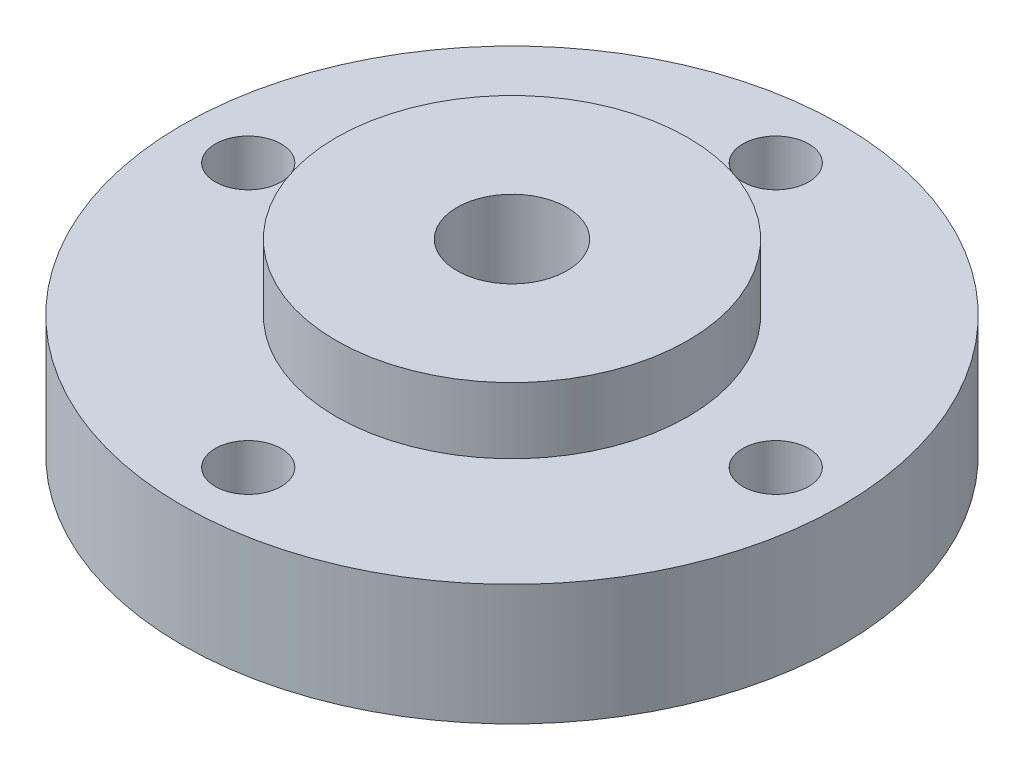
SolidWorks part; units mm, degrees
ref_plane "前视基准面" through (0, 0, 0) normal (0, 0, 1) x (1, 0, 0)
ref_plane "上视基准面" through (0, 0, 0) normal (0, 1, 0) x (1, 0, 0)
ref_plane "右视基准面" through (0, 0, 0) normal (1, 0, 0) x (0, 0, -1)
sketch "草图1" plane through (0, 0, 0) normal (0, 1, 0) x (1, 0, 0)
  line L0 (0, 0) -> (0, 18.2938) construction
  line L1 (0, 0) -> (19.7965, 0) construction
  circle A0 centre (0, 0) radius 6 construction
  circle A1 centre (0, 0) radius 12 construction
  circle A2 centre (0, 0) radius 2
  circle A3 centre (0, 6) radius 1.5
  circle A4 centre (6, 0) radius 1.5
  circle A5 centre (0, -6) radius 1.5
  circle A6 centre (-6, 0) radius 1.5
  circle A7 centre (0, 0) radius 15
  circle A8 centre (0, 12) radius 1.5
  circle A9 centre (12, 0) radius 1.5
  circle A10 centre (0, -12) radius 1.5
  circle A11 centre (-12, 0) radius 1.5
  point P16 (0, 0)
  point P28 (0, 0)
  dimension "D1" = 12
  dimension "D2" = 24
  dimension "D3" = 4
  dimension "D4" = 3
  dimension "D6" = 30
  dimension "D8" = 3
  dimension "D7" = 90
  dimension "D5" = 4
  dimension "D9" = 4
extrude "凸台-拉伸1" add sketch "草图1" along normal blind 3
sketch "草图2" plane through (0, 0, 0) normal (0, -1, 0) x (1, 0, 0)
  circle A0 centre (0, 0) radius 8
  dimension "D1" = 16
extrude "凸台-拉伸2" add sketch "草图2" along normal blind 4.25 and the other way blind 7.25
sketch "草图5" plane through (0, 3, 0) normal (0, 1, 0) x (1, 0, 0)
  circle A4 centre (0, 0) radius 15
extrude "凸台-拉伸3" add sketch "草图5" along normal blind 1.25 and the other way blind 4.25
sketch "草图3" plane through (0, 3, 0) normal (0, 1, 0) x (1, 0, 0)
  line L2 (0, 0) -> (3.05, 0) construction
  circle A2 centre (0, 0) radius 2.5
  dimension "D1" = 5
extrude "切除-拉伸1" cut sketch "草图3" against normal blind 16.5 and the other way blind 5
sketch "草图7" plane through (0, 7.25, 0) normal (0, 1, 0) x (1, 0, 0)
  line L0 (0, 12) -> (0, -12) construction
  line L1 (-12, 0) -> (12, 0) construction
  circle A0 centre (0, 12) radius 1.5
  circle A1 centre (-12, 0) radius 1.5
  circle A2 centre (12, 0) radius 1.5
  circle A3 centre (0, -12) radius 1.5
  dimension "D3" = 3
  dimension "D4" = 3
  dimension "D5" = 3
  dimension "D6" = 3
  dimension "D1" = 24
  dimension "D2" = 24
extrude "切除-拉伸4" cut sketch "草图7" against normal blind 14
sketch "草图9" plane through (0, -4.25, 0) normal (0, -1, 0) x (1, 0, 0)
  circle A0 centre (0, 0) radius 5
  dimension "D1" = 10
extrude "切除-拉伸6" cut sketch "草图9" against normal blind 5
